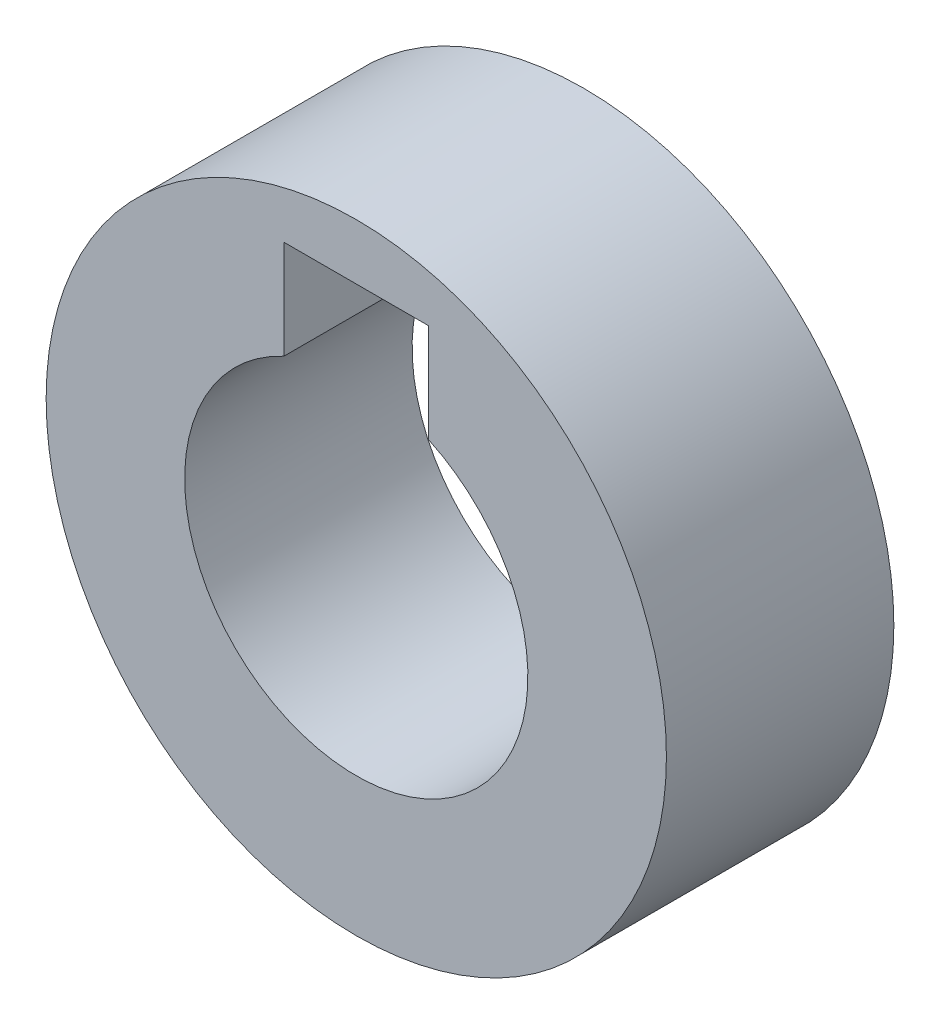
SolidWorks part; units mm, degrees
ref_plane "Ebene vorne" through (0, 0, 0) normal (0, 0, 1) x (1, 0, 0)
ref_plane "Ebene oben" through (0, 0, 0) normal (0, 1, 0) x (1, 0, 0)
ref_plane "Ebene rechts" through (0, 0, 0) normal (1, 0, 0) x (0, 0, -1)
sketch "Skizze1" plane through (0, 0, 0) normal (0, 0, 1) x (1, 0, 0)
  line L1 (-1.75, 2.15) -> (1.75, 2.15)
  line L2 (-1.75, 2.15) -> (-1.75, 6.15)
  line L3 (-1.75, 6.15) -> (1.75, 6.15)
  line L4 (1.75, 2.15) -> (1.75, 6.15)
  line L5 (-1.75, 2.15) -> (1.75, 6.15) construction
  line L6 (-1.75, 6.15) -> (1.75, 2.15) construction
  circle A0 centre (0, 0) radius 4.15
  circle A1 centre (0, 0) radius 7.5
  point P4 (0, 4.15)
  dimension "D1" = 8.3
  dimension "D2" = 15
  dimension "D3" = 3.5
  dimension "D4" = 4
extrude "Aufsatz-Linear austragen1" add sketch "Skizze1" along normal blind 5.5 contours A1 A0 L2 L3 L4
